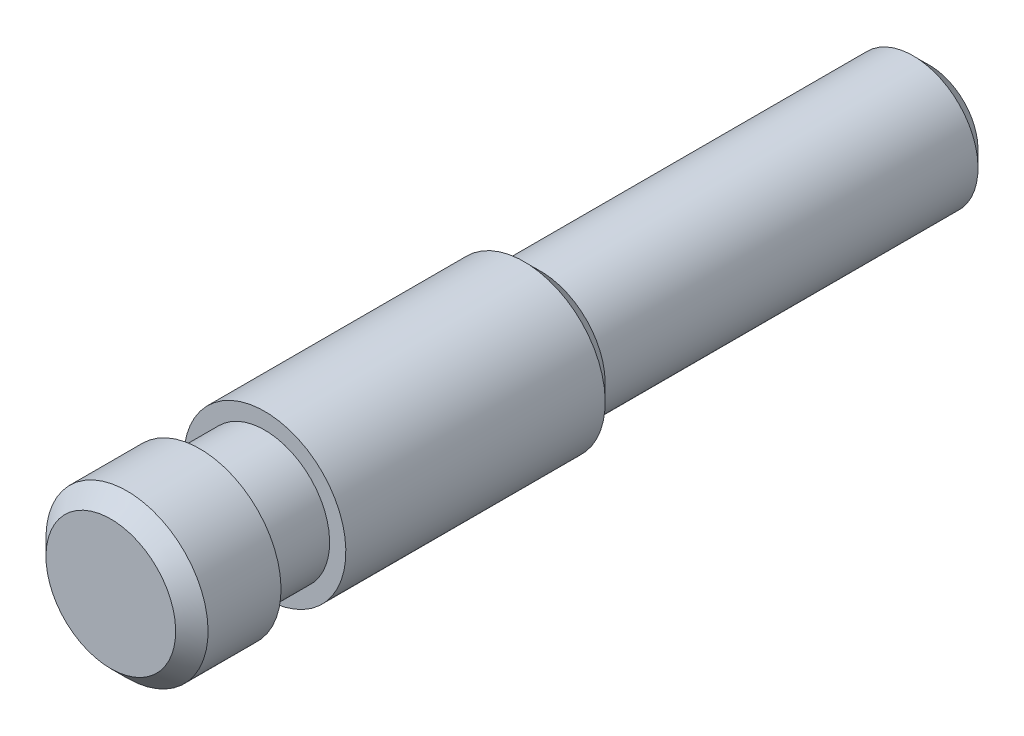
SolidWorks part; units mm, degrees
ref_plane "Plan de face" through (0, 0, 0) normal (0, 0, 1) x (1, 0, 0)
ref_plane "Plan de dessus" through (0, 0, 0) normal (0, 1, 0) x (1, 0, 0)
ref_plane "Plan de droite" through (0, 0, 0) normal (1, 0, 0) x (0, 0, -1)
sketch "Esquisse1" plane through (0, 0, 0) normal (1, 0, 0) x (0, 0, -1)
  line L0 (11, 4) -> (-12, 4)
  line L2 (-13, 5) -> (-29, 5)
  line L3 (-29, 5) -> (-29, 4)
  line L4 (-29, 4) -> (-33, 4)
  line L5 (-33, 4) -> (-33, 5)
  line L6 (-33, 5) -> (-37.5, 5)
  line L7 (-38.5, 4) -> (-38.5, 0)
  line L8 (-38.5, 0) -> (12, 0)
  line L9 (12, 0) -> (12, 3)
  line L10 (12, 3) -> (11, 4)
  line L11 (-13, 5) -> (-12, 4)
  line L12 (-37.5, 5) -> (-38.5, 4)
  point P0 (12, 4)
  point P8 (-38.5, 5)
  point P11 (0, 4)
  point P16 (0, 0)
  point P17 (0, 0)
  dimension "D1" = 4
  dimension "D2" = 17
  dimension "D3" = 5
  dimension "D4" = 4
  dimension "D5" = 5.5
  dimension "D6" = 225
  dimension "D7" = 24
  dimension "D9" = 12
revolve "Révolution1" add sketch "Esquisse1" angle 360 about L8
